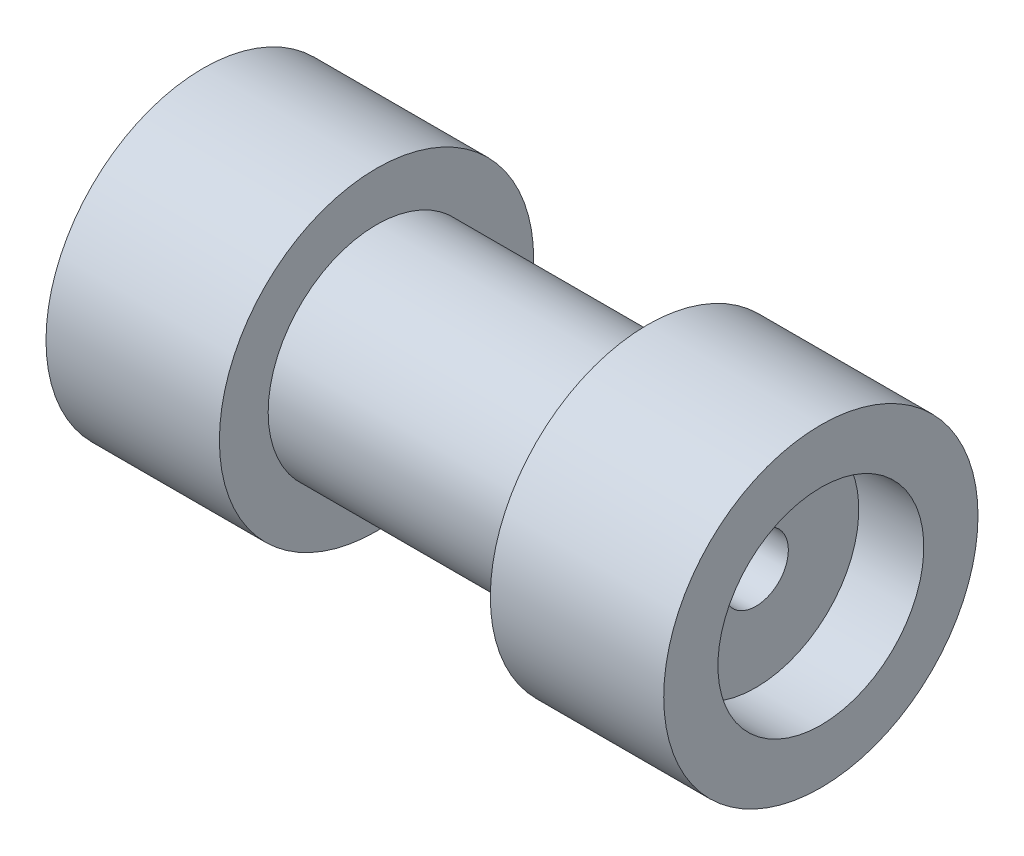
SolidWorks part; units mm, degrees
ref_plane "Front Plane" through (0, 0, 0) normal (0, 0, 1) x (1, 0, 0)
ref_plane "Top Plane" through (0, 0, 0) normal (0, 1, 0) x (1, 0, 0)
ref_plane "Right Plane" through (0, 0, 0) normal (1, 0, 0) x (0, 0, -1)
sketch "Sketch1" plane through (0, 0, 0) normal (0, 0, 1) x (1, 0, 0)
  line L0 (-41.2732, 0) -> (44.9867, 0) construction
  line L1 (0, 20.4244) -> (0, -23.7135) construction
  line L2 (-12.5, 10) -> (12.5, 10)
  line L3 (12.5, 10) -> (12.5, 14.5)
  line L4 (12.5, 14.5) -> (28.5, 14.5)
  line L5 (28.5, 14.5) -> (28.5, 9.5)
  line L6 (28.5, 9.5) -> (22.5, 9.5)
  line L7 (22.5, 9.5) -> (22.5, 0)
  line L8 (-28.5, 14.5) -> (-28.5, 9.5)
  line L9 (-28.5, 9.5) -> (-22.5, 9.5)
  line L10 (-12.5, 14.5) -> (-28.5, 14.5)
  line L11 (-12.5, 10) -> (-12.5, 14.5)
  line L12 (-22.5, 9.5) -> (-22.5, 0)
  line L13 (-22.5, 0) -> (22.5, 0)
  point P7 (0, 10)
  point P8 (25.5, 9.5)
  dimension "D1" = 12.5
  dimension "D2" = 10
  dimension "D3" = 10
  dimension "D4" = 9.5
  dimension "D5" = 5
  dimension "D6" = 6
revolve "Revolve1" add sketch "Sketch1" angle 360 about L13
sketch "Sketch2" plane through (-22.5, 0, 0) normal (-1, 0, 0) x (0, 0, 1)
  circle A0 centre (0, 0) radius 3
  dimension "D1" = 6
extrude "Cut-Extrude1" cut sketch "Sketch2" against normal through all
